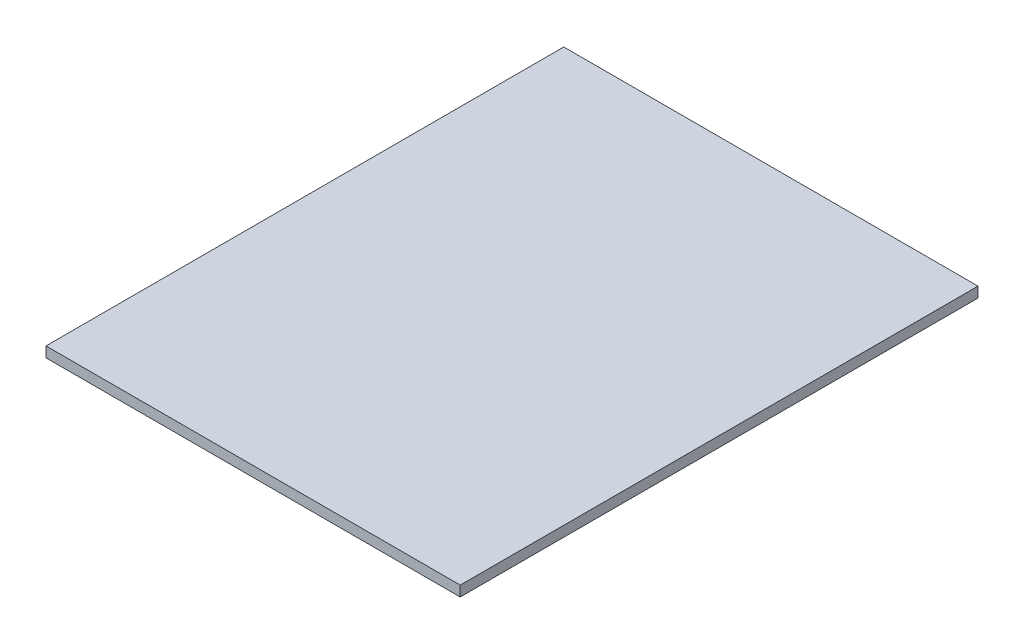
SolidWorks part; units mm, degrees
material "Бук"
ref_plane "Спереди" through (0, 0, 0) normal (0, 0, 1) x (1, 0, 0)
ref_plane "Сверху" through (0, 0, 0) normal (0, 1, 0) x (1, 0, 0)
ref_plane "Справа" through (0, 0, 0) normal (1, 0, 0) x (0, 0, -1)
sketch "Эскиз1" plane through (0, 0, 0) normal (0, 1, 0) x (1, 0, 0)
  line L1 (0, 0) -> (400, 0)
  line L2 (0, 0) -> (0, 500)
  line L3 (0, 500) -> (400, 500)
  line L4 (400, 0) -> (400, 500)
  dimension "D1" = 500
  dimension "D2" = 400
extrude "Бобышка-Вытянуть1" add sketch "Эскиз1" along normal blind 10
